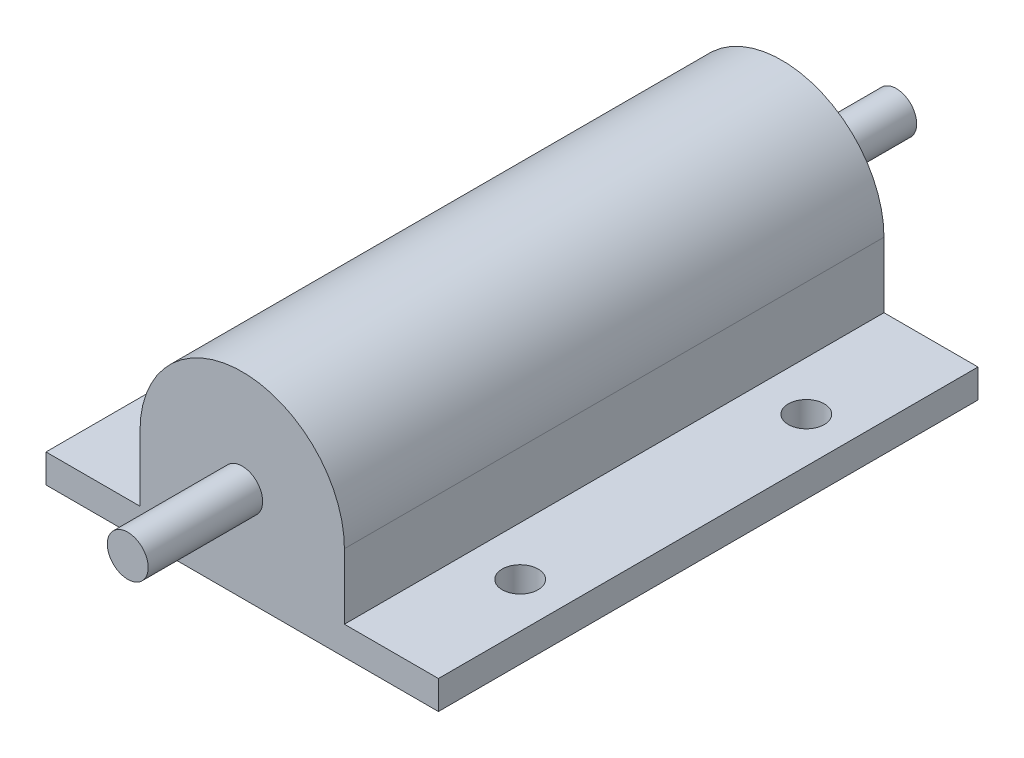
SolidWorks part; units mm, degrees
ref_plane "Front Plane" through (0, 0, 0) normal (0, 0, 1) x (1, 0, 0)
ref_plane "Top Plane" through (0, 0, 0) normal (0, 1, 0) x (1, 0, 0)
ref_plane "Right Plane" through (0, 0, 0) normal (1, 0, 0) x (0, 0, -1)
sketch "Sketch1" plane through (0, 0, 0) normal (0, 0, 1) x (1, 0, 0)
  line L0 (12.5, -8) -> (24, -8)
  line L1 (-24, -11.5) -> (24, -11.5)
  line L2 (-24, -11.5) -> (-24, -8)
  line L3 (-24, -8) -> (-12.5, -8)
  line L4 (24, -11.5) -> (24, -8)
  line L5 (-12.5, 0) -> (-12.5, -8)
  line L6 (12.5, 0) -> (12.5, -8)
  arc A0 (12.5, 0) -> (-12.5, 0) centre (0, 0) ccw
  dimension "D1" = 24
  dimension "D2" = 3.5
  dimension "D3" = 11.5
  dimension "D4" = 48
extrude "Boss-Extrude1" add sketch "Sketch1" along normal mid plane 66
sketch "Sketch2" plane through (0, -8, 0) normal (0, 1, 0) x (1, 0, 0)
  line L1 (18.5, -17.5) -> (-18.5, -17.5) construction
  line L2 (18.5, -17.5) -> (18.5, 17.5) construction
  line L3 (18.5, 17.5) -> (-18.5, 17.5) construction
  line L4 (-18.5, -17.5) -> (-18.5, 17.5) construction
  line L5 (18.5, -17.5) -> (-18.5, 17.5) construction
  line L6 (18.5, 17.5) -> (-18.5, -17.5) construction
  circle A0 centre (-18.5, 17.5) radius 2.2
  circle A1 centre (-18.5, -17.5) radius 2.2
  circle A2 centre (18.5, -17.5) radius 2.2
  circle A3 centre (18.5, 17.5) radius 2.2
  point P0 (0, 0)
  dimension "D1" = 4.4
  dimension "D2" = 35
  dimension "D3" = 37
extrude "Cut-Extrude1" cut sketch "Sketch2" against normal through all
sketch "Sketch3" plane through (0, 0, 33) normal (0, 0, 1) x (1, 0, 0)
  circle A0 centre (0, 0) radius 2.5
  dimension "D1" = 5
extrude "Boss-Extrude2" add sketch "Sketch3" along normal offset from surface (14 mm away) 47 up to plane "Front Plane"
mirror "Mirror5" about plane through (0, 0, 0) normal (0, 0, 1) of "Boss-Extrude2"
